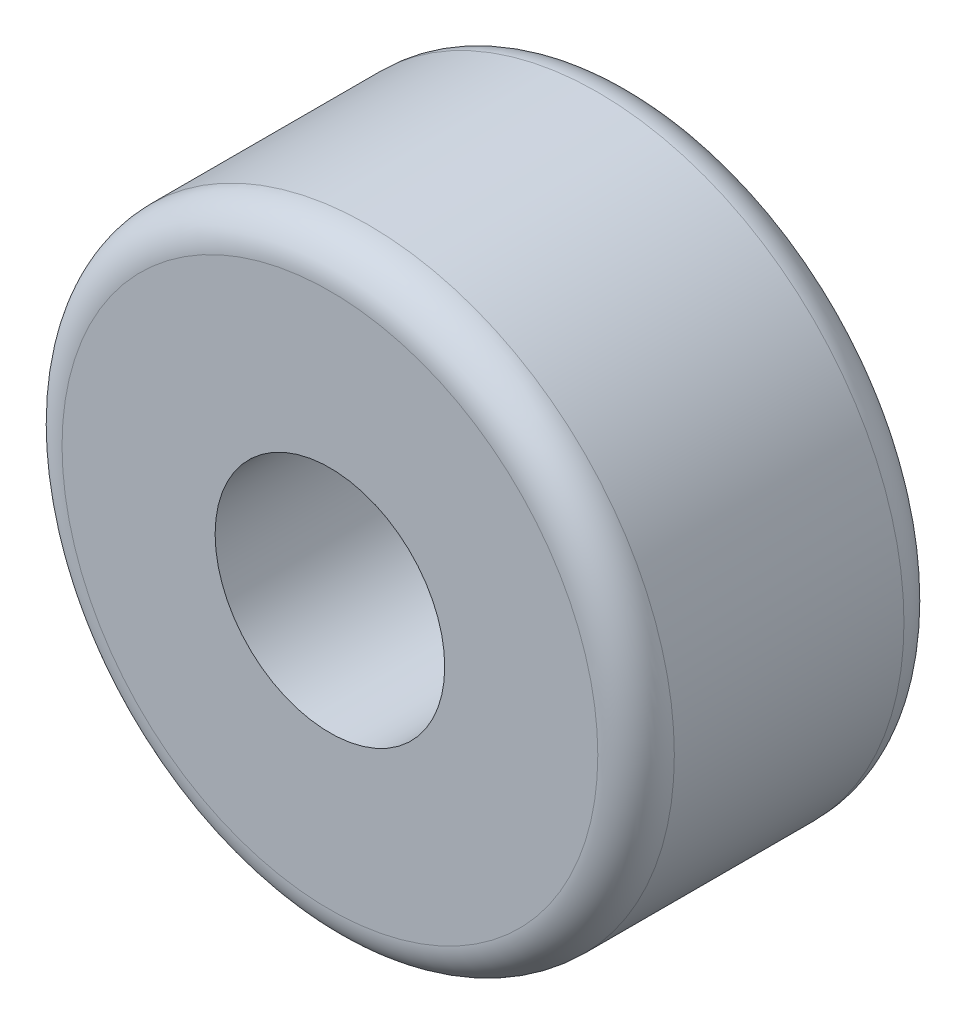
SolidWorks part; units mm, degrees
ref_plane "Front Plane" through (0, 0, 0) normal (0, 0, 1) x (1, 0, 0)
ref_plane "Top Plane" through (0, 0, 0) normal (0, 1, 0) x (1, 0, 0)
ref_plane "Right Plane" through (0, 0, 0) normal (1, 0, 0) x (0, 0, -1)
sketch "Sketch1" plane through (0, 0, 0) normal (0, 0, 1) x (1, 0, 0)
  circle A0 centre (0.0287, 0.0337) radius 8
  circle A1 centre (0.0287, 0.0337) radius 3
  dimension "D1" = 16
  dimension "D2" = 6
extrude "Boss-Extrude1" add sketch "Sketch1" along normal blind 8
fillet "Fillet1" radius 1 2 edges at (8.0287, 0.0337, 0) (8.0287, 0.0337, 8)
